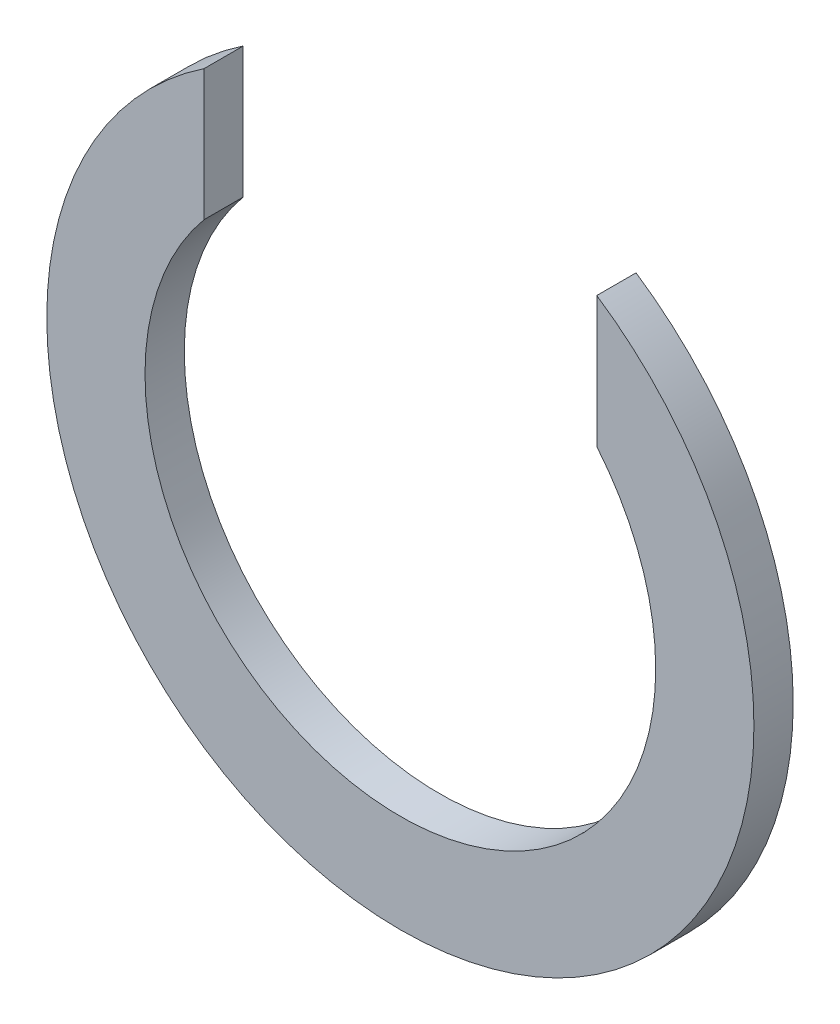
SolidWorks part; units mm, degrees
ref_plane "Front Plane" through (0, 0, 0) normal (0, 0, 1) x (1, 0, 0)
ref_plane "Top Plane" through (0, 0, 0) normal (0, 1, 0) x (1, 0, 0)
ref_plane "Right Plane" through (0, 0, 0) normal (1, 0, 0) x (0, 0, -1)
sketch "Esboço1" plane through (0, 0, 0) normal (0, 0, 1) x (1, 0, 0)
  line L0 (-10, 8.3066) -> (-10, 14.9666)
  line L1 (0, -55) -> (0, 55) construction
  line L2 (10, 8.3066) -> (10, 14.9666)
  arc A0 (-10, 8.3066) -> (10, 8.3066) centre (0, 0) ccw
  arc A1 (-10, 14.9666) -> (10, 14.9666) centre (0, 0) ccw
  point P6 (-10.1939, 8.0675)
  dimension "D1" = 26
  dimension "D2" = 5
  dimension "D3" = 10
extrude "Ressalto-extrusão1" add sketch "Esboço1" along normal blind 2
